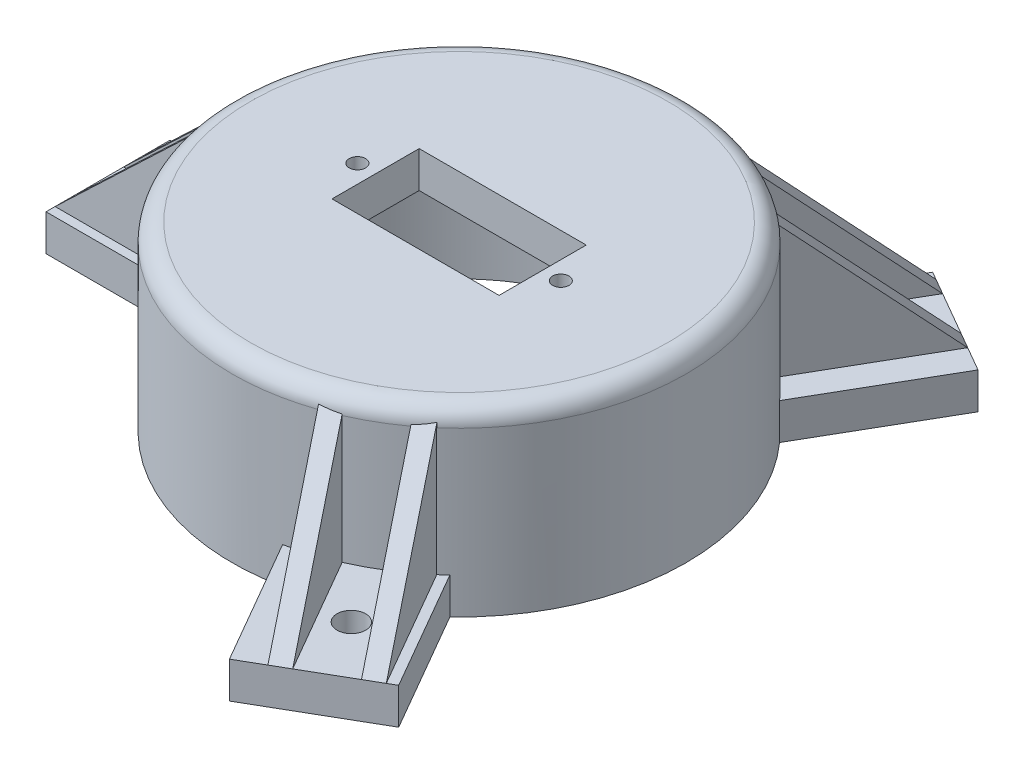
SolidWorks part; units mm, degrees
ref_plane "Front Plane" through (0, 0, 0) normal (0, 0, 1) x (1, 0, 0)
ref_plane "Top Plane" through (0, 0, 0) normal (0, 1, 0) x (1, 0, 0)
ref_plane "Right Plane" through (0, 0, 0) normal (1, 0, 0) x (0, 0, -1)
sketch "Sketch1" plane through (0, 0, 0) normal (0, 1, 0) x (1, 0, 0)
  circle A0 centre (0, 0) radius 31.75
  dimension "D1" = 63.5
extrude "Boss-Extrude1" add sketch "Sketch1" along normal blind 25.4
fillet "Fillet1" radius 2.54 1 edges at (0, 25.4, 31.75)
sketch "Sketch2" plane through (0, 0, 0) normal (0, -1, 0) x (1, 0, 0)
  circle A0 centre (0, 0) radius 26.179
extrude "Cut-Extrude1" cut sketch "Sketch2" against normal blind 20.32
sketch "Sketch3" plane through (0, 25.4, 0) normal (0, 1, 0) x (1, 0, 0)
  line L1 (-11.684, 6.096) -> (11.684, 6.096)
  line L2 (-11.684, 6.096) -> (-11.684, -6.096)
  line L3 (-11.684, -6.096) -> (11.684, -6.096)
  line L4 (11.684, 6.096) -> (11.684, -6.096)
  line L5 (-11.684, 6.096) -> (11.684, -6.096) construction
  line L6 (-11.684, -6.096) -> (11.684, 6.096) construction
  point P0 (0, 0)
  dimension "D1" = 23.368
  dimension "D2" = 12.192
extrude "Cut-Extrude2" cut sketch "Sketch3" against normal blind 20.32
sketch "Sketch4" plane through (0, 25.4, 0) normal (0, 1, 0) x (1, 0, 0)
  line L0 (-11.684, 6.096) -> (-11.684, -6.096) construction
  circle A0 centre (-14.224, 0) radius 1.143
  dimension "D1" = 2.286
  dimension "D2" = 2.54
extrude "Cut-Extrude3" cut sketch "Sketch4" against normal blind 20.32
mirror "Mirror1" about plane through (0, 0, 0) normal (1, 0, 0) of "Cut-Extrude3"
sketch "Sketch6" plane through (0, 0, 0) normal (0, -1, 0) x (1, 0, 0)
  line L1 (-27.9914, 7.3311) -> (-50.446, 7.3311)
  line L2 (-27.9914, 7.3311) -> (-27.9914, -9.9969)
  line L3 (-27.9914, -9.9969) -> (-50.446, -9.9969)
  line L4 (-50.446, 7.3311) -> (-50.446, -9.9969)
extrude "Boss-Extrude2" add sketch "Sketch6" against normal blind 5.08
ref_plane "Plane2" through (0, 0, 4.7911) normal (0, 0, 1) x (1, 0, 0)
sketch "Sketch11" plane through (0, 0, 4.7911) normal (0, 0, 1) x (1, 0, 0)
  line L0 (-50.446, 5.08) -> (-31.7337, 22.86)
  line L1 (-31.75, 22.86) -> (31.75, 22.86) construction
rib "Rib1" sketch "Sketch11" sketch "Sketch11" thickness 2.54 extrusion direction parallel to sketch draft on no parameters "D1"=2.54
mirror "Mirror2" about plane through (0, 0, 0) normal (0, 0, 1) of "Rib1"
pattern_circular "CirPattern1" count 3 over 360 about axis through (0, 0, 0) along (0, 1, 0) of "Mirror2", "Boss-Extrude2", "Rib1"
sketch "Sketch12" plane through (0, 5.08, 0) normal (0, 1, 0) x (1, 0, 0)
  circle A0 centre (-41.1818, 0) radius 2
  dimension "D1" = 4
extrude "Cut-Extrude4" cut sketch "Sketch12" against normal blind 5.08
pattern_circular "CirPattern2" count 3 over 360 about axis through (0, 0, 0) along (0, 1, 0) of "Cut-Extrude4"
